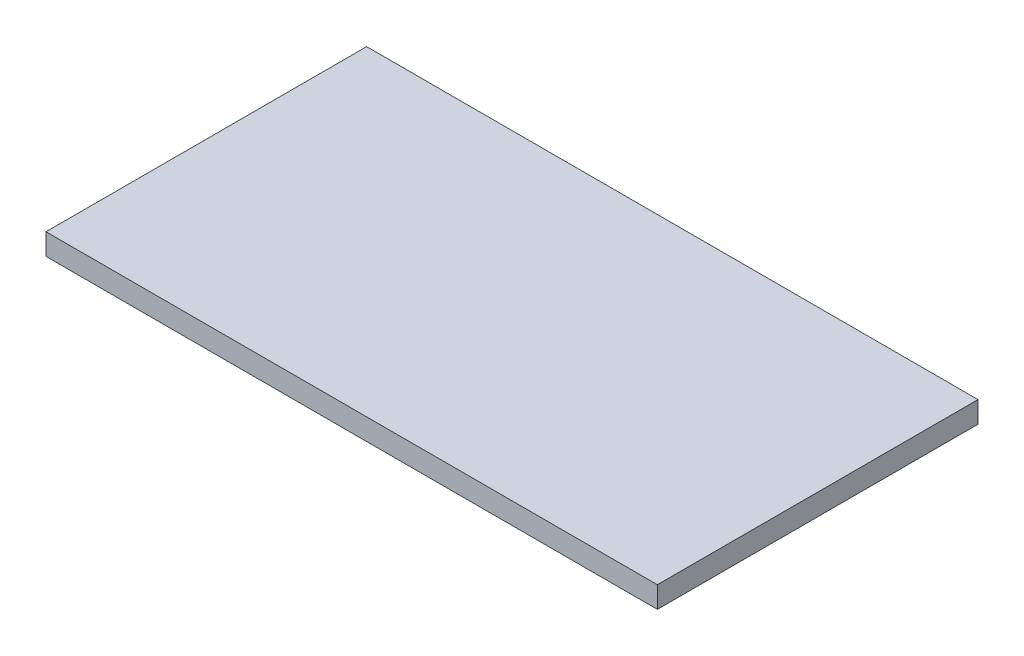
SolidWorks part; units mm, degrees
ref_plane "Front Plane" through (0, 0, 0) normal (0, 0, 1) x (1, 0, 0)
ref_plane "Top Plane" through (0, 0, 0) normal (0, 1, 0) x (1, 0, 0)
ref_plane "Right Plane" through (0, 0, 0) normal (1, 0, 0) x (0, 0, -1)
sketch "PCB" plane through (0, 0, 0) normal (0, 1, 0) x (1, 0, 0)
  line L1 (0, 0) -> (28.6, 0)
  line L2 (0, 0) -> (0, -15)
  line L3 (0, -15) -> (28.6, -15)
  line L4 (28.6, 0) -> (28.6, -15)
  dimension "D1" = 15
  dimension "D2" = 28.6
extrude "Boss-Extrude1" add sketch "PCB" along normal blind 1
sketch "Sketch2" [suppressed] plane through (0, 1, 0) normal (0, 1, 0) x (1, 0, 0)
  line L0 (14.8, -1.8) -> (20.8, -1.8) construction
  line L1 (14.8, 0) -> (20.8, 0)
  line L2 (14.8, -3.6) -> (20.8, -3.6)
  line L3 (28.6, 0) -> (0, 0) construction
  line L4 (22.6, -1.8) -> (28.6, -1.8) construction
  line L5 (28.6, -15) -> (28.6, 0) construction
  line L6 (13, -1.8) -> (0, -1.8) construction
  line L7 (0, 0) -> (0, -15) construction
  arc A0 (14.8, 0) -> (14.8, -3.6) centre (14.8, -1.8) ccw
  arc A1 (20.8, -3.6) -> (20.8, 0) centre (20.8, -1.8) ccw
  point P2 (17.8, -1.8)
  dimension "D3" = 1.8
  dimension "D1" = 6
  dimension "D2" = 6
  dimension "D4" = 13
